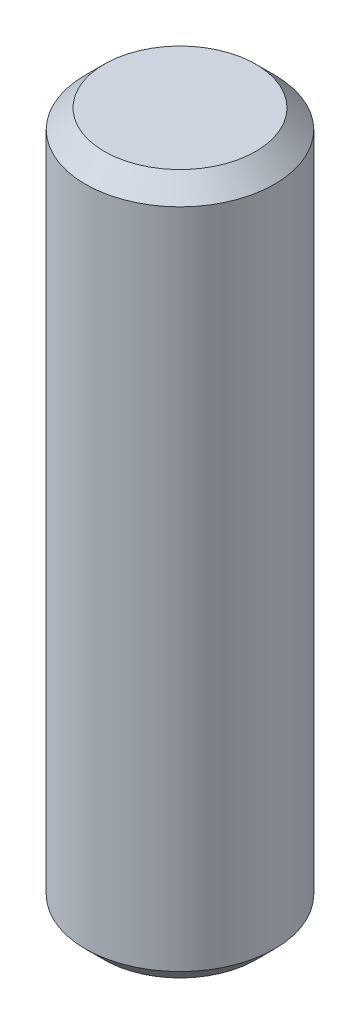
SolidWorks part; units mm, degrees
ref_plane "Front Plane" through (0, 0, 0) normal (0, 0, 1) x (1, 0, 0)
ref_plane "Top Plane" through (0, 0, 0) normal (0, 1, 0) x (1, 0, 0)
ref_plane "Right Plane" through (0, 0, 0) normal (1, 0, 0) x (0, 0, -1)
sketch "Sketch2" plane through (0, 0, 0) normal (0, 0, 1) x (1, 0, 0)
  line L1 (0, 0) -> (10, 0)
  line L2 (0, 0) -> (0, 74)
  line L3 (0, 74) -> (10, 74)
  line L4 (10, 0) -> (10, 74)
  dimension "D1" = 10
  dimension "D2" = 74
revolve "Revolve1" add sketch "Sketch2" angle 360 about L2
cosmetic thread "Cosmetic Thread1" parameters "D1"=24, "D2"=17.252
cosmetic thread "Cosmetic Thread2" parameters "D1"=24, "D2"=17.252
chamfer "Chamfer1" distance 2 angle 45 2 edges at (0, 0, -10) (0, 74, -10)
